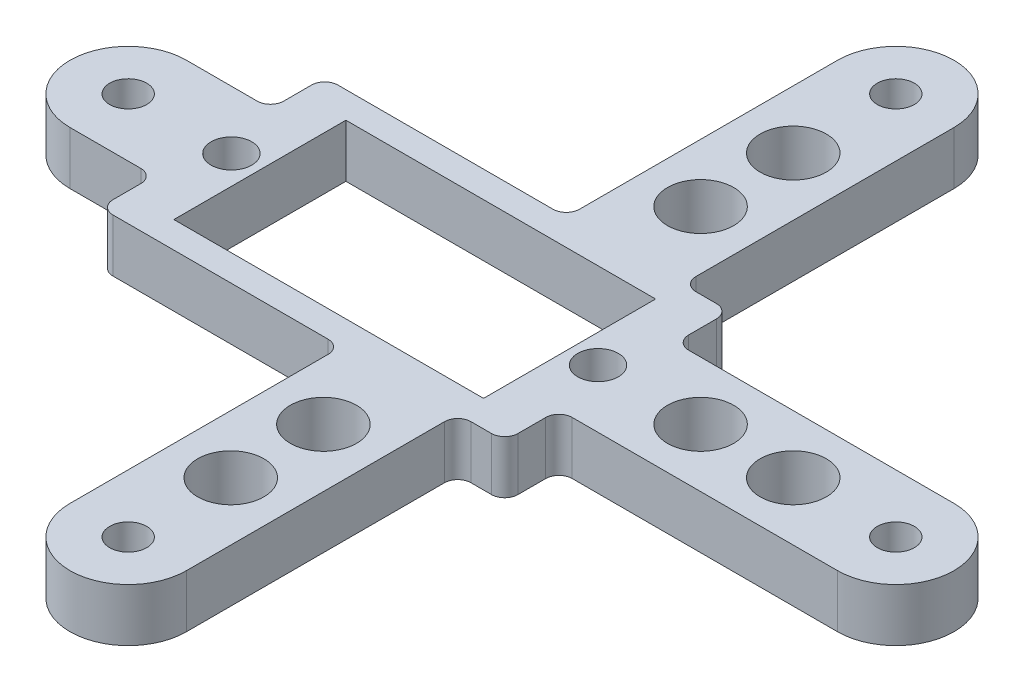
SolidWorks part; units mm, degrees
ref_plane "Front Plane" through (0, 0, 0) normal (0, 0, 1) x (1, 0, 0)
ref_plane "Top Plane" through (0, 0, 0) normal (0, 1, 0) x (1, 0, 0)
ref_plane "Right Plane" through (0, 0, 0) normal (1, 0, 0) x (0, 0, -1)
sketch "Sketch1" plane through (0, 0, 0) normal (0, 1, 0) x (1, 0, 0)
  line L0 (0, 0) -> (0, 40) construction
  line L1 (-3.2648, 40.9493) -> (-12.9904, 7.5)
  line L2 (3.4, 40) -> (12.9904, 7.5)
  line L3 (-37.0955, -17.6472) -> (-12.9904, 7.5)
  line L4 (0, 0) -> (34.641, -20)
  line L5 (0, 0) -> (-34.641, -20)
  line L6 (-33.8307, -23.302) -> (0, -15)
  line L7 (0, -15) -> (33.8307, -23.302)
  line L8 (12.9904, 7.5) -> (37.0955, -17.6472)
  line L9 (-12.9904, 7.5) -> (0, 0) construction
  line L10 (12.9904, 7.5) -> (0, 0) construction
  line L11 (0, -15) -> (0, 0) construction
  circle A0 centre (0, 40) radius 1.4
  arc A1 (3.4, 40) -> (-3.2648, 40.9493) centre (0, 40) ccw
  circle A2 centre (34.641, -20) radius 1.4
  circle A3 centre (-34.641, -20) radius 1.4
  arc A4 (-37.0955, -17.6472) -> (-33.8307, -23.302) centre (-34.641, -20) ccw
  arc A5 (33.8307, -23.302) -> (37.0955, -17.6472) centre (34.641, -20) ccw
  circle A6 centre (0, 0) radius 40 construction
  point P12 (0, 11.4518)
  dimension "D1" = 2
  dimension "D2" = 2.8
  dimension "D3" = 80
  dimension "D4" = 120
  dimension "D5" = 120
  dimension "D6" = 15
sketch "Sketch2" plane through (0, 0, 0) normal (0, 1, 0) x (1, 0, 0)
  line L0 (0, 0) -> (0, 29) construction
  line L2 (29, 0) -> (0, 0) construction
  line L10 (-21.2, 0) -> (6.5, 0) construction
  line L11 (29, 4.4) -> (7.95, 4.4)
  line L12 (-19.05, -6.5) -> (4.35, -6.5)
  line L13 (-19.05, -6.5) -> (-19.05, 6.5)
  line L14 (-19.05, 6.5) -> (4.35, 6.5)
  line L15 (4.35, -6.5) -> (4.35, 6.5)
  line L16 (-19.05, -6.5) -> (4.35, 6.5) construction
  line L17 (-19.05, 6.5) -> (4.35, -6.5) construction
  line L18 (7.95, 4.4) -> (7.95, 8.5)
  line L19 (7.95, 8.5) -> (4.4, 8.5)
  line L20 (-22.65, 8.5) -> (-22.65, 4.4)
  line L21 (-22.65, 4.4) -> (-29, 4.4)
  line L22 (-29, -4.4) -> (-22.65, -4.4)
  line L23 (-22.65, -4.4) -> (-22.65, -8.5)
  line L24 (-22.65, -8.5) -> (-4.4, -8.5)
  line L25 (7.95, -8.5) -> (7.95, -4.4)
  line L26 (7.95, -4.4) -> (29, -4.4)
  line L27 (-7.35, 0) -> (-7.35, 6.5) construction
  line L28 (4.35, -6.5) -> (7.95, -8.5) construction
  line L29 (-4.4, 29) -> (-4.4, 8.5)
  line L30 (4.4, 29) -> (4.4, 8.5)
  line L31 (-4.4, -29) -> (-4.4, -8.5)
  line L32 (4.4, -29) -> (4.4, -8.5)
  line L33 (4.4, -8.5) -> (7.95, -8.5)
  line L34 (-4.4, 8.5) -> (-22.65, 8.5)
  circle A0 centre (0, 29) radius 1.4
  circle A1 centre (29, 0) radius 1.4
  circle A4 centre (0, 0) radius 29 construction
  circle A5 centre (0, -29) radius 1.4
  circle A6 centre (-29, 0) radius 1.4
  circle A10 centre (6.5, 0) radius 1.5352
  circle A11 centre (-21.2, 0) radius 1.5352
  circle A12 centre (0, 0) radius 1.5352 construction
  circle A13 centre (-29, 0) radius 4.4 construction
  circle A14 centre (29, 0) radius 4.4 construction
  circle A15 centre (0, -29) radius 4.4 construction
  circle A16 centre (0, 29) radius 4.4 construction
  arc A17 (-29, 4.4) -> (-29, -4.4) centre (-29, 0) ccw
  arc A18 (29, 4.4) -> (29, -4.4) centre (29, 0) cw
  arc A19 (-4.4, 29) -> (4.4, 29) centre (0, 29) cw
  arc A20 (-4.4, -29) -> (4.4, -29) centre (0, -29) ccw
  point P28 (-7.35, 0)
  point P42 (0, 0)
  point P45 (7.2764, -8.1258)
  dimension "D2" = 2.8
  dimension "D3" = 3
  dimension "D1" = 58
  dimension "D7" = 3.0705
  dimension "D4" = 13
  dimension "D5" = 23.4
  dimension "D6" = 27.7
  dimension "D8" = 7.35
  dimension "D9" = 2
extrude "Boss-Extrude2" add sketch "Sketch2" along normal blind 4
sketch "Sketch3" plane through (0, 0, 0) normal (0, 1, 0) x (1, 0, 0)
  circle A0 centre (0, 21.25) radius 2.5
  circle A1 centre (0, 14.25) radius 2.5
  circle A2 centre (14.25, 0) radius 2.5
  circle A3 centre (21.25, 0) radius 2.5
  circle A4 centre (0, -14.25) radius 2.5
  circle A5 centre (0, -21.25) radius 2.5
  circle A6 centre (0, 0) radius 14.25 construction
  circle A7 centre (0, 0) radius 21.25 construction
  point P16 (0, 0)
  point P17 (0, 0)
  point P18 (0, 0)
  point P19 (0, 0)
  point P20 (0, 0)
  point P21 (0, 21.25)
  point P22 (0, 0)
  point P23 (0, 0)
  point P24 (0, 0)
  point P25 (0, 0)
  dimension "D1" = 5
  dimension "D2" = 7
  dimension "D3" = 42.5
extrude "Cut-Extrude3" cut sketch "Sketch3" against normal through all and the other way through all contours A0 | A1 | A2 | A3 | A4 | A5
fillet "Fillet1" radius 1 12 edges at (-4.4, 2, 8.5) (-22.65, 2, 8.5) (-22.65, 2, 4.4) (-22.65, 2, -4.4) (-22.65, 2, -8.5) (-4.4, 2, -8.5) (4.4, 2, -8.5) (7.95, 2, -8.5) (7.95, 2, -4.4) (7.95, 2, 4.4) (7.95, 2, 8.5) (4.4, 2, 8.5)
